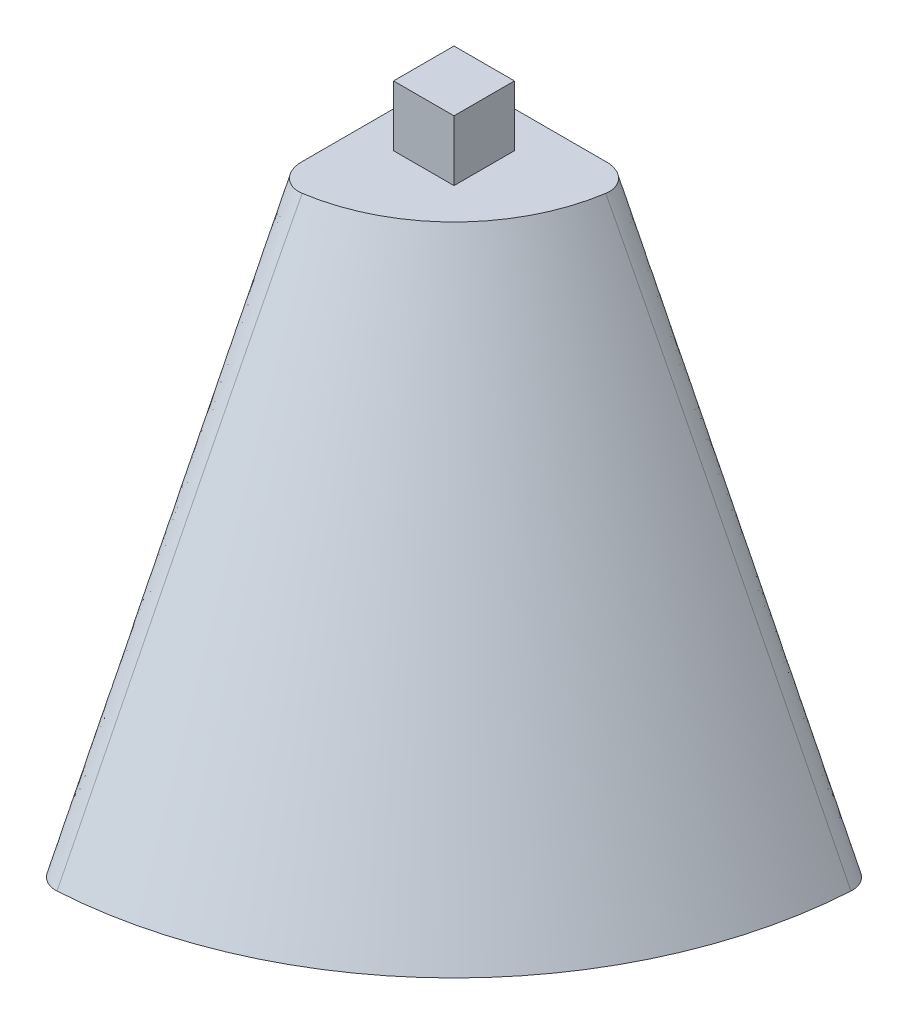
SolidWorks part; units mm, degrees
ref_plane "Front Plane" through (0, 0, 0) normal (0, 0, 1) x (1, 0, 0)
ref_plane "Top Plane" through (0, 0, 0) normal (0, 1, 0) x (1, 0, 0)
ref_plane "Right Plane" through (0, 0, 0) normal (1, 0, 0) x (0, 0, -1)
sketch "Sketch1" plane through (0, 0, 0) normal (0, 0, 1) x (1, 0, 0)
  line L0 (0, 0) -> (15, 0)
  line L1 (0, 0) -> (0, -40)
  line L2 (0, -40) -> (35, -40)
  line L3 (35, -40) -> (15, 0)
  dimension "D1" = 15
  dimension "D2" = 40
  dimension "D3" = 35
revolve "Revolve1" add sketch "Sketch1" angle 90 about L1
fillet "Fillet2" radius 2 1 edges at (0, -20, 25)
fillet "Fillet3" radius 2 1 edges at (25, -20, 0)
fillet "Fillet4" radius 3 1 edges at (0, -20, 0)
sketch "Sketch2" plane through (0, 0, 0) normal (0, 1, 0) x (1, 0, 0)
  line L7 (3, -3) -> (8, -3)
  line L8 (3, -3) -> (3, -8)
  line L9 (3, -8) -> (8, -8)
  line L10 (8, -3) -> (8, -8)
  point P0 (0, 0)
  dimension "D1" = 5
extrude "Boss-Extrude1" add sketch "Sketch2" along normal blind 5
